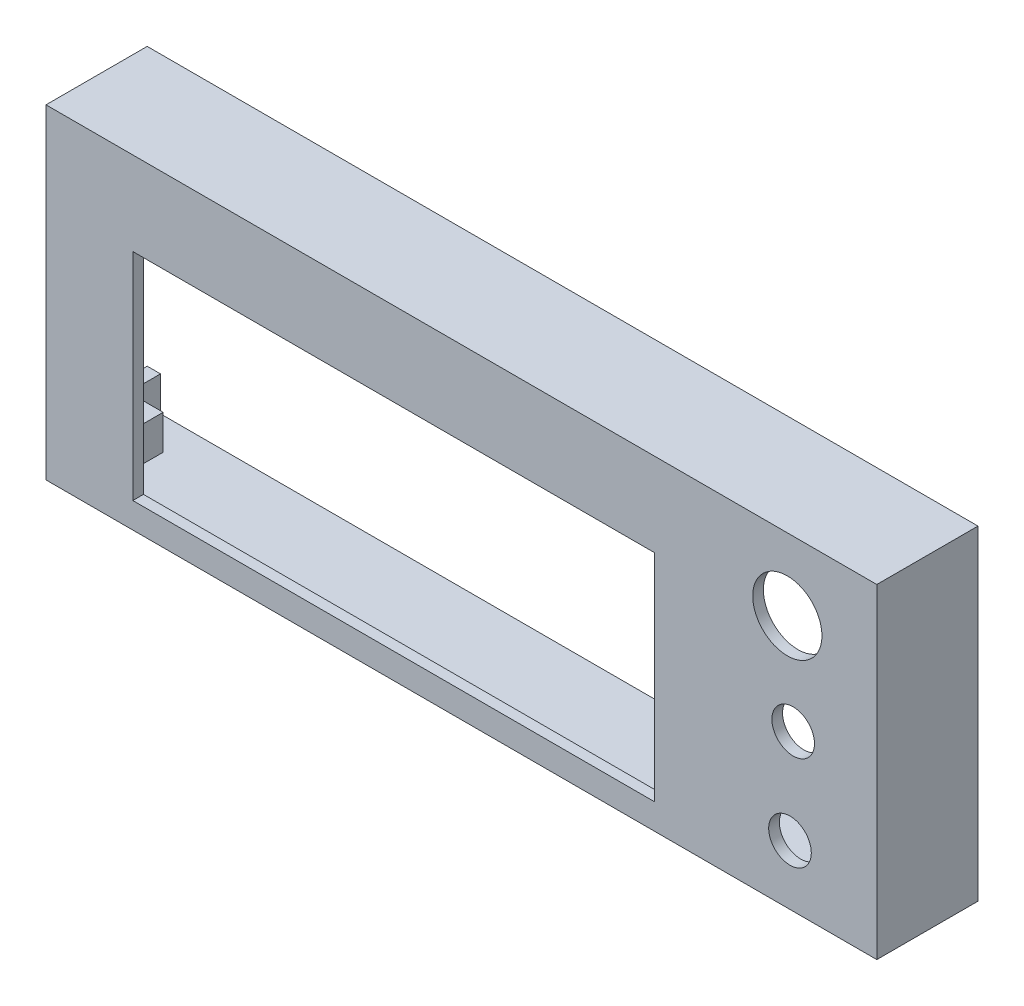
SolidWorks part; units mm, degrees
material "ABS"
ref_plane "Front Plane" through (0, 0, 0) normal (0, 0, 1) x (1, 0, 0)
ref_plane "Top Plane" through (0, 0, 0) normal (0, 1, 0) x (1, 0, 0)
ref_plane "Right Plane" through (0, 0, 0) normal (1, 0, 0) x (0, 0, -1)
sketch "Sketch1" plane through (0, 0, 0) normal (0, 0, 1) x (1, 0, 0)
  line L0 (-93, 10.5) -> (-78, 10.5)
  line L1 (93, 30.5) -> (-93, 30.5)
  line L2 (93, 30.5) -> (93, 10.5)
  line L3 (78, -30.5) -> (-78, -30.5)
  line L4 (-93, 30.5) -> (-93, 10.5)
  line L5 (93, 30.5) -> (-93, -30.5) construction
  line L6 (93, -30.5) -> (-93, 30.5) construction
  line L7 (-78, 10.5) -> (-78, -30.5)
  line L8 (93, 10.5) -> (78, 10.5)
  line L9 (78, 10.5) -> (78, -30.5)
  point P0 (0, 0)
  dimension "D1" = 186
  dimension "D2" = 61
  dimension "D3" = 20
  dimension "D4" = 15
  dimension "D5" = 15
  dimension "D6" = 93
  dimension "D7" = 30.5
  dimension "D8" = 61
extrude "Boss-Extrude1" add sketch "Sketch1" along normal blind 24
sketch "Sketch2" plane through (0, 0, 0) normal (0, 0, -1) x (-1, 0, 0)
  line L0 (-78, -30.5) -> (-78, 10.5) construction
  line L1 (75.5, -28) -> (-75.5, -28)
  line L2 (75.5, -28) -> (75.5, 28)
  line L3 (75.5, 28) -> (-75.5, 28)
  line L4 (-75.5, -28) -> (-75.5, 28)
  line L5 (75.5, -28) -> (-75.5, 28) construction
  line L6 (75.5, 28) -> (-75.5, -28) construction
  line L7 (-93, 30.5) -> (93, 30.5) construction
  point P0 (0, 0)
  dimension "D1" = 2.5
  dimension "D2" = 2.5
extrude "Cut-Extrude1" cut sketch "Sketch2" against normal blind 22
sketch "Sketch3" plane through (0, 0, 0) normal (0, 0, -1) x (-1, 0, 0)
  line L1 (78, 30.5) -> (-78, 30.5)
  line L2 (78, 30.5) -> (78, -30.5)
  line L3 (78, -30.5) -> (-78, -30.5)
  line L4 (-78, 30.5) -> (-78, -30.5)
  line L5 (78, 30.5) -> (-78, -30.5) construction
  line L6 (78, -30.5) -> (-78, 30.5) construction
  point P0 (0, 0)
extrude "Cut-Extrude2" cut sketch "Sketch3" against normal blind 5
sketch "Sketch4" plane through (0, 0, 24) normal (0, 0, 1) x (1, 0, 0)
  line L0 (-78, 10.5) -> (-78, -30.5) construction
  line L1 (-61.7, -25.7) -> (36.3, -25.7)
  line L2 (-61.7, -25.7) -> (-61.7, 14.8)
  line L3 (-61.7, 14.8) -> (36.3, 14.8)
  line L4 (36.3, -25.7) -> (36.3, 14.8)
  line L5 (-78, -30.5) -> (78, -30.5) construction
  line L7 (93, 30.5) -> (-93, 30.5) construction
  line L9 (78, -30.5) -> (78, 10.5) construction
  circle A0 centre (61.2, 17) radius 6.5
  circle A1 centre (62.3, -1.25) radius 4
  circle A2 centre (61.7, -19.3) radius 4
  dimension "D5" = 13
  dimension "D6" = 8
  dimension "D7" = 8
  dimension "D1" = 98
  dimension "D2" = 40.5
  dimension "D3" = 16.3
  dimension "D4" = 4.8
  dimension "D8" = 16.8
  dimension "D9" = 18.25
  dimension "D10" = 11.2
  dimension "D11" = 13.5
  dimension "D12" = 15.7
  dimension "D13" = 16.3
extrude "Cut-Extrude3" cut sketch "Sketch4" against normal blind 4
hole_wizard "CBORE for M4 Hex Socket Head Cap Screw1" positions "Sketch5" profile "Sketch6" counterbore size "M4" standard "DIN" end condition through all
sketch "Sketch5" plane through (0, 0, 24) normal (0, 0, 1) x (1, 0, 0)
  line L0 (-93, 10.5) -> (-78, 10.5) construction
  line L1 (-93, 30.5) -> (-93, 10.5) construction
  point P0 (-85, 20.5)
  point P2 (85, 20.3761)
  dimension "D1" = 10
  dimension "D2" = 170
  dimension "D3" = 8
sketch "Sketch6" plane through (-85, 20.5, 24) normal (1, 0, 0) x (0, -1, 0)
  line L0 (0, 0) -> (0, 24)
  line L1 (0, 24) -> (2.25, 24)
  line L3 (2.25, 24) -> (2.25, 4.4)
  line L4 (2.25, 4.4) -> (4, 4.4)
  line L5 (4, 4.4) -> (4, 0)
  line L7 (4, 0) -> (0, 0)
  line L11 (0, -6.35) -> (0, 107.95) construction
  dimension "Thru Hole Dia." = 4.5
  dimension "Thru Hole Depth" = 24
  dimension "C'Bore Dia." = 8
  dimension "C'Bore Depth" = 4.4
sketch "Sketch7" plane through (0, 0, 22) normal (0, 0, -1) x (-1, 0, 0)
  line L1 (-75.5, 28) -> (-69, 28)
  line L2 (-75.5, 28) -> (-75.5, 21.5)
  line L3 (-75.5, 21.5) -> (-69, 21.5)
  line L4 (-69, 28) -> (-69, 21.5)
  line L5 (-75.5, -28) -> (-69, -28)
  line L6 (-75.5, -28) -> (-75.5, -21.5)
  line L7 (-75.5, -21.5) -> (-69, -21.5)
  line L8 (-69, -28) -> (-69, -21.5)
  line L9 (75.5, 28) -> (69, 28)
  line L10 (75.5, 28) -> (75.5, 21.5)
  line L11 (75.5, 21.5) -> (69, 21.5)
  line L12 (69, 28) -> (69, 21.5)
  line L13 (75.5, -28) -> (69, -28)
  line L14 (75.5, -28) -> (75.5, -21.5)
  line L15 (75.5, -21.5) -> (69, -21.5)
  line L16 (69, -28) -> (69, -21.5)
  dimension "D1" = 6.5
  dimension "D2" = 6.5
  dimension "D3" = 6.5
  dimension "D4" = 6.5
  dimension "D5" = 6.5
  dimension "D6" = 6.5
  dimension "D7" = 6.5
  dimension "D8" = 6.5
extrude "Boss-Extrude2" add sketch "Sketch7" along normal blind 11
hole_wizard "Ø2.0mm Dowel Hole1" positions "Sketch8" profile "Sketch9" hole size "Ø2.0" standard "DIN"
sketch "Sketch8" plane through (0, 0, 11) normal (0, 0, -1) x (-1, 0, 0)
  point P0 (-72.25, 24.75)
  point P2 (-72.25, -24.75)
  point P4 (72.25, 24.75)
  point P6 (72.25, -24.75)
  dimension "D1" = 49.5
  dimension "D2" = 49.5
  dimension "D3" = 144.5
  dimension "D4" = 144.5
  dimension "D5" = 72.25
  dimension "D6" = 24.75
  dimension "D7" = 24.75
  dimension "D8" = 72.25
sketch "Sketch9" plane through (72.25, 24.75, 11) normal (1, 0, 0) x (0, 1, 0)
  line L0 (0, 0) -> (0, 8.6009)
  line L1 (0, 8.6009) -> (1, 8)
  line L2 (1, 8) -> (1, 0)
  line L5 (1, 0) -> (0, 0)
  line L10 (0, 8.6009) -> (-1, 8) construction
  line L11 (0, -6.35) -> (0, 107.95) construction
  dimension "Hole Dia." = 2
  dimension "Hole Depth" = 8
  dimension "Drill Angle" = 118
sketch "Sketch13" plane through (0, 0, 0) normal (0, 0, -1) x (-1, 0, 0)
  line L1 (-93, 30.5) -> (-78, 30.5)
  line L2 (-93, 30.5) -> (-93, 10.5)
  line L3 (-93, 10.5) -> (-78, 10.5)
  line L4 (-78, 30.5) -> (-78, 10.5)
  line L5 (93, 30.5) -> (78, 30.5)
  line L6 (93, 30.5) -> (93, 10.5)
  line L7 (93, 10.5) -> (78, 10.5)
  line L8 (78, 30.5) -> (78, 10.5)
extrude "Cut-Extrude6" cut sketch "Sketch13" against normal blind 24
sketch "Sketch14" plane through (-78, 0, 0) normal (-1, 0, 0) x (0, 0, 1)
  line L0 (5, -30.5) -> (5, 30.5) construction
  line L1 (5, -21.5) -> (11, -21.5)
  line L2 (5, -21.5) -> (5, 9.5)
  line L3 (5, 9.5) -> (11, 9.5)
  line L4 (11, -21.5) -> (11, 9.5)
  line L5 (24, -30.5) -> (5, -30.5) construction
  dimension "D1" = 31
  dimension "D2" = 6
  dimension "D3" = 9
extrude "Cut-Extrude7" cut sketch "Sketch14" against normal blind 3
